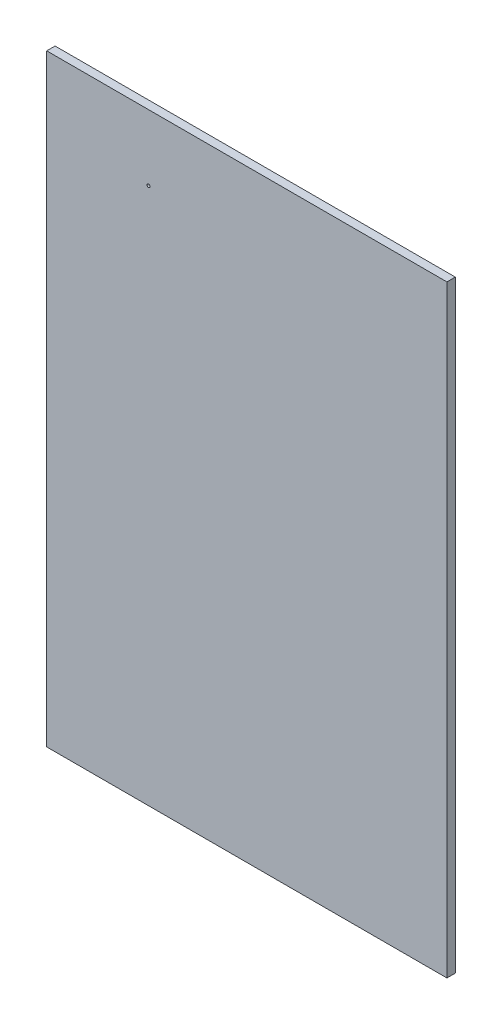
SolidWorks part; units mm, degrees
ref_plane "Front Plane" through (0, 0, 0) normal (0, 0, 1) x (1, 0, 0)
ref_plane "Top Plane" through (0, 0, 0) normal (0, 1, 0) x (1, 0, 0)
ref_plane "Right Plane" through (0, 0, 0) normal (1, 0, 0) x (0, 0, -1)
sketch "Sketch1" plane through (0, 0, 0) normal (0, 0, 1) x (1, 0, 0)
  line L1 (-600, 900) -> (600, 900)
  line L2 (-600, 900) -> (-600, -900)
  line L3 (-600, -900) -> (600, -900)
  line L4 (600, 900) -> (600, -900)
  line L5 (-600, 900) -> (600, -900) construction
  line L6 (-600, -900) -> (600, 900) construction
  point P0 (0, 0)
  dimension "D1" = 1200
  dimension "D2" = 1800
extrude "Boss-Extrude1" add sketch "Sketch1" along normal blind 25
sketch "Sketch2" plane through (0, 0, 25) normal (0, 0, 1) x (1, 0, 0)
  line L0 (600, 900) -> (-600, 900) construction
  line L1 (-600, 900) -> (-600, -900) construction
  circle A0 centre (-296, 703) radius 4.5
  dimension "D1" = 9
  dimension "D2" = 197
  dimension "D3" = 304
extrude "Cut-Extrude1" cut sketch "Sketch2" against normal through all
sketch "Sketch3" plane through (0, 0, 25) normal (0, 0, 1) x (1, 0, 0)
  line L0 (600, 900) -> (-600, 900) construction
  line L1 (600, -900) -> (600, 900) construction
  point P0 (400, 730)
  dimension "D1" = 170
  dimension "D2" = 200
sketch "Sketch5" plane through (600, 0, 0) normal (1, 0, 0) x (0, 0, -1)
  line L1 (-908.7026, 1234.4388) -> (1009.6153, 1234.4388)
  line L2 (-908.7026, 1234.4388) -> (-908.7026, -1380.1026)
  line L3 (-908.7026, -1380.1026) -> (1009.6153, -1380.1026)
  line L4 (1009.6153, 1234.4388) -> (1009.6153, -1380.1026)
extrude "Cut-Extrude2" cut sketch "Sketch5" against normal blind 5
